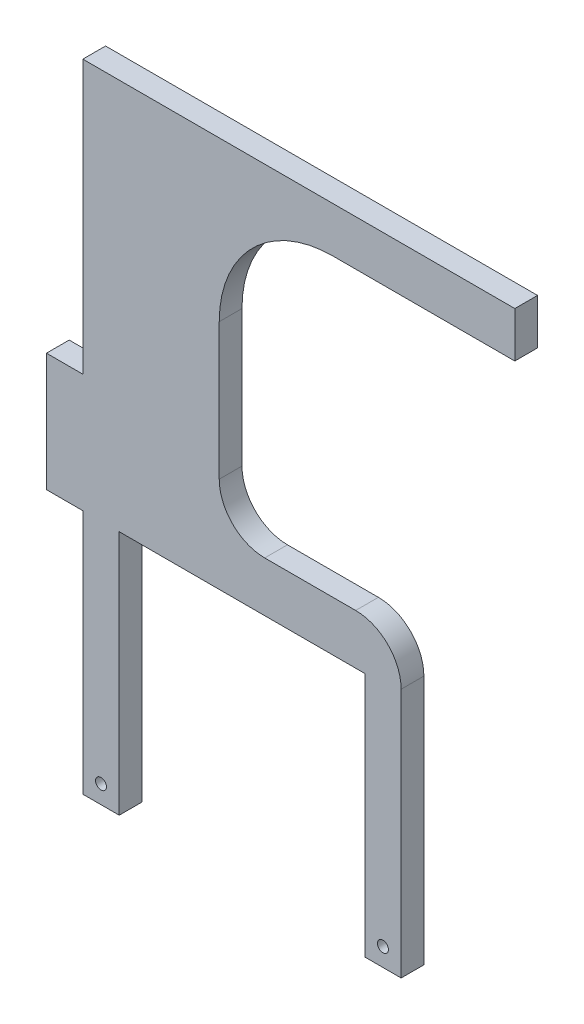
SolidWorks part; units mm, degrees
ref_plane "Plan de face" through (0, 0, 0) normal (0, 0, 1) x (1, 0, 0)
ref_plane "Plan de dessus" through (0, 0, 0) normal (0, 1, 0) x (1, 0, 0)
ref_plane "Plan de droite" through (0, 0, 0) normal (1, 0, 0) x (0, 0, -1)
sketch "Esquisse1" plane through (0, 0, 0) normal (0, 0, 1) x (1, 0, 0)
  line L36 (0, 0) -> (0, 54)
  line L41 (0, 140) -> (120, 140)
  line L42 (120, 140) -> (120, 130)
  line L43 (120, 130) -> (30, 130)
  line L44 (30, 130) -> (30, 80)
  line L45 (30, 80) -> (70, 80)
  line L46 (70, 80) -> (70, 0)
  line L47 (70, 0) -> (62, 0)
  line L48 (62, 0) -> (62, 54)
  line L49 (62, 54) -> (8, 54)
  line L50 (0, 0) -> (8, 0)
  line L51 (8, 0) -> (8, 54)
  line L52 (0, 80) -> (-8, 80)
  line L53 (-8, 80) -> (-8, 54)
  line L54 (-8, 54) -> (0, 54)
  line L55 (0, 80) -> (0, 140)
  dimension "D2" = 8
  dimension "D3" = 54
  dimension "D4" = 8
  dimension "D5" = 10
  dimension "D6" = 140
  dimension "D7" = 8
  dimension "D8" = 120
  dimension "D10" = 90
  dimension "D11" = 50
  dimension "D12" = 54
extrude "Boss.-Extru.1" add sketch "Esquisse1" along normal blind 5
sketch "Esquisse2" plane through (0, 0, 5) normal (0, 0, 1) x (1, 0, 0)
  line L0 (0, 0) -> (8, 0) construction
  line L1 (8, 0) -> (8, 54) construction
  line L2 (62, 0) -> (70, 0) construction
  line L3 (70, 0) -> (70, 80) construction
  circle A0 centre (4, 4) radius 1
  circle A1 centre (66, 4) radius 1
  dimension "D1" = 4
  dimension "D3" = 2
  dimension "D6" = 2
  dimension "D2" = 4
  dimension "D4" = 4
  dimension "D5" = 4
fillet "Congé1" [suppressed] radius 10
fillet "Congé2" radius 25 1 edges at (30, 130, 2.5)
sketch "Esquisse5" plane through (0, 0, 5) normal (0, 0, 1) x (1, 0, 0)
  line L0 (70, 80) -> (30, 80) construction
  line L1 (70, 80) -> (30, 80)
  line L2 (70, 80) -> (70, 65)
  line L3 (70, 65) -> (30, 65)
  line L4 (30, 80) -> (30, 65)
  line L5 (30, 80) -> (30, 105) construction
  point P5 (30.0415, 80)
  dimension "D2" = 15
extrude "Enlèv. mat.-Extru.1" cut sketch "Esquisse5" against normal up to surface (5 mm away) up to face at (36.1072, 69.7752, 0)
sketch "Esquisse6" plane through (0, 0, 5) normal (0, 0, 1) x (1, 0, 0)
  line L0 (55, 130) -> (120, 130) construction
  line L1 (120, 140) -> (112, 140)
  line L2 (120, 140) -> (120, 130)
  line L3 (120, 130) -> (112, 130)
  line L4 (112, 140) -> (112, 130)
  dimension "D1" = 8
extrude "Enlèv. mat.-Extru.2" [suppressed] cut sketch "Esquisse6" against normal up to surface (5 mm away)
fillet "Congé3" radius 10 2 edges at (70, 65, 2.5) (30, 65, 2.5)
fillet "Congé4" [suppressed] radius 10
sketch "Esquisse7" plane through (0, 0, 5) normal (0, 0, 1) x (1, 0, 0)
  line L0 (0, 54) -> (0, 0) construction
  line L1 (120, 140) -> (0, 140)
  line L2 (120, 140) -> (120, 80)
  line L3 (120, 80) -> (0, 80)
  line L4 (0, 140) -> (0, 80)
  line L6 (0, 80) -> (-8, 80) construction
extrude "Enlèv. mat.-Extru.3" [suppressed] cut sketch "Esquisse7" against normal up to surface (5 mm away)
sketch "Esquisse8" [suppressed] plane through (0, 0, 5) normal (0, 0, 1) x (1, 0, 0)
  line L5 (0, 80) -> (-15, 80)
  line L6 (-15, 80) -> (-15, 54)
  line L7 (-15, 54) -> (0, 54)
  line L8 (0, 80) -> (0, 0) construction
  line L9 (8, 54) -> (62, 54) construction
  line L10 (0, 80) -> (0, 54)
  line L18 (45, 80) -> (0, 80)
  line L19 (0, 80) -> (0, 0)
  line L20 (0, 0) -> (8, 0)
  line L21 (8, 0) -> (8, 54)
  line L22 (8, 54) -> (62, 54)
  line L23 (62, 54) -> (62, 0)
  line L24 (62, 0) -> (70, 0)
  line L25 (70, 0) -> (70, 60)
  line L26 (45, 80) -> (0, 80)
  line L27 (0, 54) -> (0, 0)
  line L28 (0, 0) -> (8, 0)
  line L29 (8, 0) -> (8, 54)
  line L30 (8, 54) -> (62, 54)
  line L31 (62, 54) -> (62, 0)
  line L32 (62, 0) -> (70, 0)
  line L33 (70, 0) -> (70, 60)
  arc A3 (70, 60) -> (61.2017, 69.9275) centre (60, 60) ccw
  arc A4 (53.7017, 74.9275) -> (61.2017, 69.9275) centre (62.4034, 79.8551) ccw
  arc A5 (53.7017, 74.9275) -> (45, 80) centre (45, 70) ccw
  arc A6 (70, 60) -> (61.2017, 69.9275) centre (60, 60) ccw
  arc A7 (53.7017, 74.9275) -> (61.2017, 69.9275) centre (62.4034, 79.8551) ccw
  arc A8 (53.7017, 74.9275) -> (45, 80) centre (45, 70) ccw
  dimension "D1" = 15
  dimension "D2" = 0
extrude "Enlèv. mat.-Extru.5" cut sketch "Esquisse2" against normal blind 10
hole_wizard "Dégagement M21" positions "Esquisse3" profile "Esquisse4" hole size "M2" standard "ISO" end condition through all
sketch "Esquisse3" plane through (0, 0, 5) normal (0, 0, 1) x (1, 0, 0)
  point P0 (4, 4)
  point P3 (66, 4)
sketch "Esquisse4" plane through (4, 4, 5) normal (1, 0, 0) x (0, -1, 0)
  line L0 (0, 0) -> (0, 5)
  line L1 (0, 5) -> (1.2, 5)
  line L2 (1.2, 5) -> (1.2, 0)
  line L5 (1.2, 0) -> (0, 0)
  line L11 (0, -6.35) -> (0, 107.95) construction
  dimension "Diamètre du perçage jusqu'au prochain" = 2.4
  dimension "Profondeur du perçage jusqu'au prochain" = 5
sketch "Esquisse9" plane through (0, 0, 5) normal (0, 0, 1) x (1, 0, 0)
  line L0 (120, 140) -> (0, 140) construction
  line L1 (120, 130) -> (95, 130)
  line L2 (120, 130) -> (120, 140)
  line L3 (120, 140) -> (95, 140)
  line L4 (95, 130) -> (95, 140)
  dimension "D1" = 25
extrude "Enlèv. mat.-Extru.6" cut sketch "Esquisse9" against normal up to surface (5 mm away) up to face at (5.2, 4, 0)
